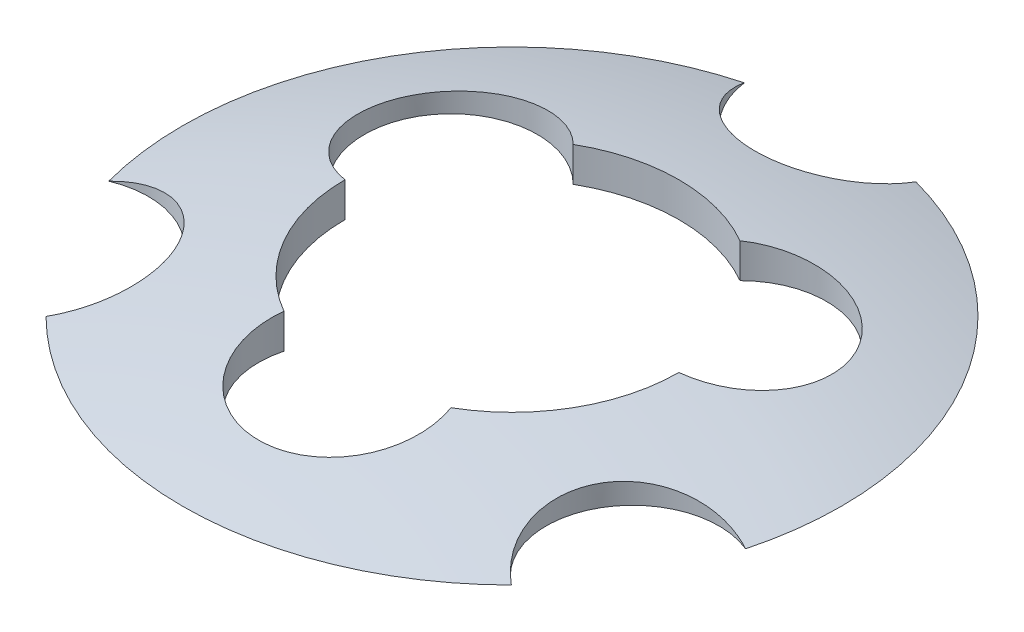
SolidWorks part; units mm, degrees
ref_plane "Alzado" through (0, 0, 0) normal (0, 0, 1) x (1, 0, 0)
ref_plane "Planta" through (0, 0, 0) normal (0, 1, 0) x (1, 0, 0)
ref_plane "Vista lateral" through (0, 0, 0) normal (1, 0, 0) x (0, 0, -1)
sketch "Croquis1" plane through (0, 0, 0) normal (0, 0, 1) x (1, 0, 0)
  line L0 (0, 0) -> (0, 49.6809) construction
  line L1 (0, 0) -> (9.525, 0)
  line L2 (0, 1) -> (4.825, 1)
  line L3 (0, 0) -> (0, 1)
  arc A0 (9.525, 0) -> (4.825, 1) centre (0, -33.2225) ccw
  dimension "D1" = 9.525
  dimension "D2" = 4.825
  dimension "D3" = 1
revolve "Revolución1" add sketch "Croquis1" angle 360 about L0
sketch "Croquis2" plane through (0, 1, 0) normal (0, 1, 0) x (1, 0, 0)
  line L0 (0, 0) -> (0, 9.525) construction
  line L1 (0, 0) -> (-4.1786, 2.4125) construction
  arc A0 (-4.825, -0.0025) -> (-2.4146, -4.1773) centre (0, 0) ccw
  circle A2 centre (0, 0) radius 4.825 construction
  circle A3 centre (0, 0) radius 9.525 construction
  circle A4 centre (0, 9.525) radius 2.5
  circle A5 centre (8.2489, -4.7625) radius 2.5
  circle A6 centre (-8.2489, -4.7625) radius 2.5
  arc A7 (-2.4104, 4.1798) -> (-4.825, -0.0025) centre (-4.1786, 2.4125) ccw
  arc A8 (4.825, -0.0025) -> (2.4104, 4.1798) centre (4.1786, 2.4125) ccw
  arc A9 (-2.4146, -4.1773) -> (2.4146, -4.1773) centre (0, -4.825) ccw
  arc A10 (2.4146, -4.1773) -> (4.825, -0.0025) centre (0, 0) ccw
  arc A11 (2.4104, 4.1798) -> (-2.4104, 4.1798) centre (0, 0) ccw
  circle A12 centre (0, 0) radius 4.825 construction
  point P16 (0, 0)
  point P23 (0, 0)
  dimension "D1" = 5
  dimension "D3" = 5
  dimension "D4" = 60
  dimension "D2" = 3
  dimension "D5" = 3
extrude "Cortar-Extruir1" cut sketch "Croquis2" against normal up to next
